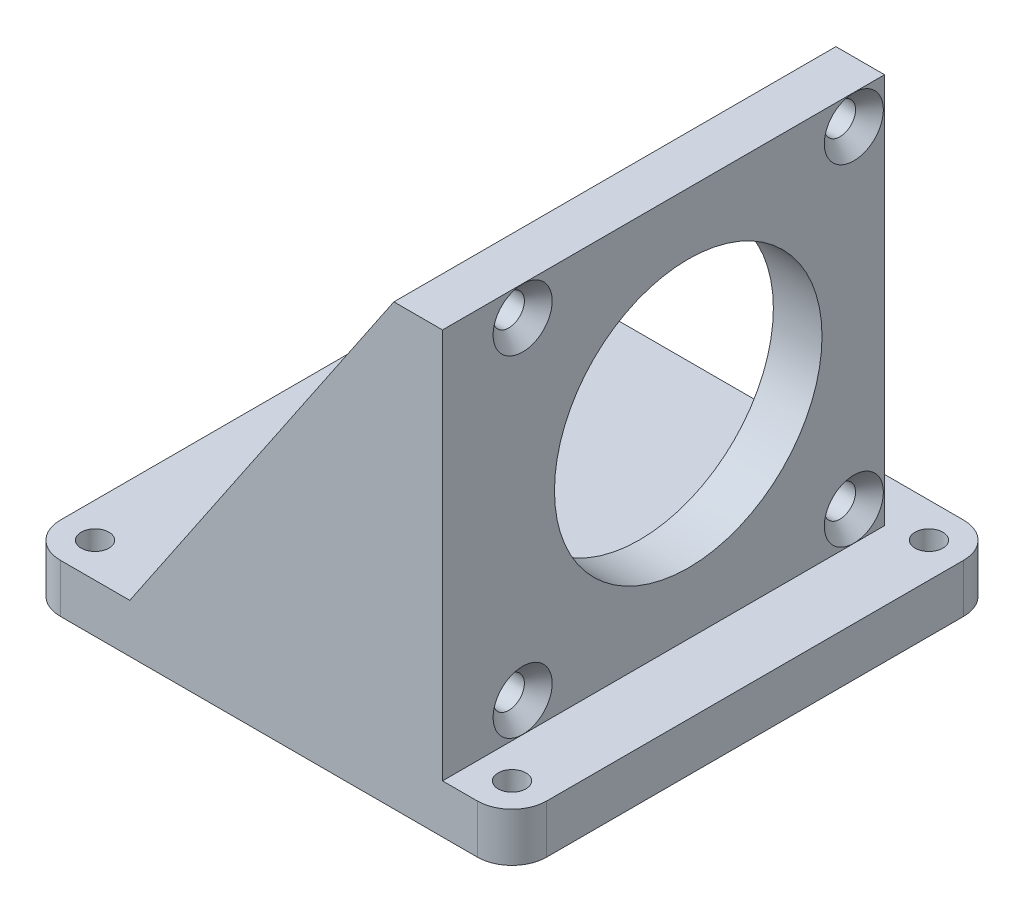
SolidWorks part; units mm, degrees
ref_plane "Front Plane" through (0, 0, 0) normal (0, 0, 1) x (1, 0, 0)
ref_plane "Top Plane" through (0, 0, 0) normal (0, 1, 0) x (1, 0, 0)
ref_plane "Right Plane" through (0, 0, 0) normal (1, 0, 0) x (0, 0, -1)
sketch "Sketch1" plane through (0, 0, 0) normal (1, 0, 0) x (0, 0, -1)
  line L0 (-27.8887, -28.1) -> (28.6113, -28.1)
  line L1 (-27.8887, 28.1) -> (28.6113, -28.1) construction
  line L2 (-27.8887, -28.1) -> (28.6113, 28.1) construction
  line L3 (0.3613, 15.5259) -> (0.3613, -16.4933) construction
  line L4 (-27.8887, 28.1) -> (28.6113, 28.1)
  line L5 (-27.8887, -28.1) -> (-27.8887, 28.1)
  line L6 (28.6113, 28.1) -> (28.6113, -28.1)
  line L7 (-23.4682, 23.8295) -> (0.3613, 0) construction
  line L8 (0.3613, 0) -> (-25.2507, 0) construction
  circle A0 centre (0.3613, 0) radius 19.25
  circle A1 centre (-23.4682, 23.8295) radius 2.25
  circle A2 centre (24.1908, 23.8295) radius 2.25
  circle A3 centre (24.1908, -23.8295) radius 2.25
  circle A4 centre (-23.4682, -23.8295) radius 2.25
  point P0 (0.3613, 0)
  point P18 (0, 0)
  point P20 (28.6113, 0)
  dimension "D1" = 38.5
  dimension "D4" = 4.5
  dimension "D2" = 33.7
  dimension "D3" = 45
  dimension "D5" = 56.2
  dimension "D6" = 56.5
extrude "Boss-Extrude1" add sketch "Sketch1" along normal mid plane 7
sketch "Sketch2" plane through (0, -28.1, 0) normal (0, -1, 0) x (1, 0, 0)
  line L0 (3.5, 27.8887) -> (3.5, -28.6113) construction
  line L1 (-51.5, 35) -> (8.5, 35)
  line L2 (-56.5, 30) -> (-56.5, -30)
  line L3 (-51.5, -35) -> (8.5, -35)
  line L4 (13.5, 30) -> (13.5, -30)
  line L5 (-56.5, 35) -> (13.5, -35) construction
  line L6 (-56.5, -35) -> (13.5, 35) construction
  line L7 (-46.2065, 0) -> (35.5376, 0) construction
  line L8 (-21.5, 18.8232) -> (-21.5, -16.6978) construction
  circle A0 centre (8.5, 30) radius 2
  circle A1 centre (8.5, -30) radius 2
  circle A2 centre (-51.5, 30) radius 2
  circle A3 centre (-51.5, -30) radius 2
  arc A4 (13.5, -30) -> (8.5, -35) centre (8.5, -30) cw
  arc A5 (-51.5, -35) -> (-56.5, -30) centre (-51.5, -30) cw
  arc A6 (-56.5, 30) -> (-51.5, 35) centre (-51.5, 30) cw
  arc A7 (13.5, 30) -> (8.5, 35) centre (8.5, 30) ccw
  point P0 (-21.5, 0)
  point P16 (0, 0)
  point P17 (0, 0)
  point P34 (8.4167, 29.9167)
  dimension "D3" = 4
  dimension "D4" = 5
  dimension "D1" = 70
  dimension "D2" = 10
extrude "Boss-Extrude2" add sketch "Sketch2" along normal blind 7
sketch "Sketch4" plane through (0, 0, 0) normal (0, 0, 1) x (1, 0, 0)
  line L0 (-41.5, -28.1) -> (-3.5, 28.1)
  line L1 (-3.5, 28.1) -> (3.5, 28.1)
  line L2 (3.5, 28.1) -> (3.5, -28.1)
  line L3 (3.5, -28.1) -> (-41.5, -28.1)
  line L4 (8.5, -28.1) -> (-51.5, -28.1) construction
  point P4 (0, 0)
  point P9 (-39.7236, -28.1)
  dimension "D1" = 45
extrude "Boss-Extrude3" add sketch "Sketch4" along normal up to surface (7.1113 mm away) from surface at 35
chamfer "Chamfer1" distance 2 angle 45 4 edges at (3.5, -23.8295, -26.4408) (3.5, 23.8295, -21.9408) (3.5, -23.8295, 25.7182) (3.5, 23.8295, 21.2182)
